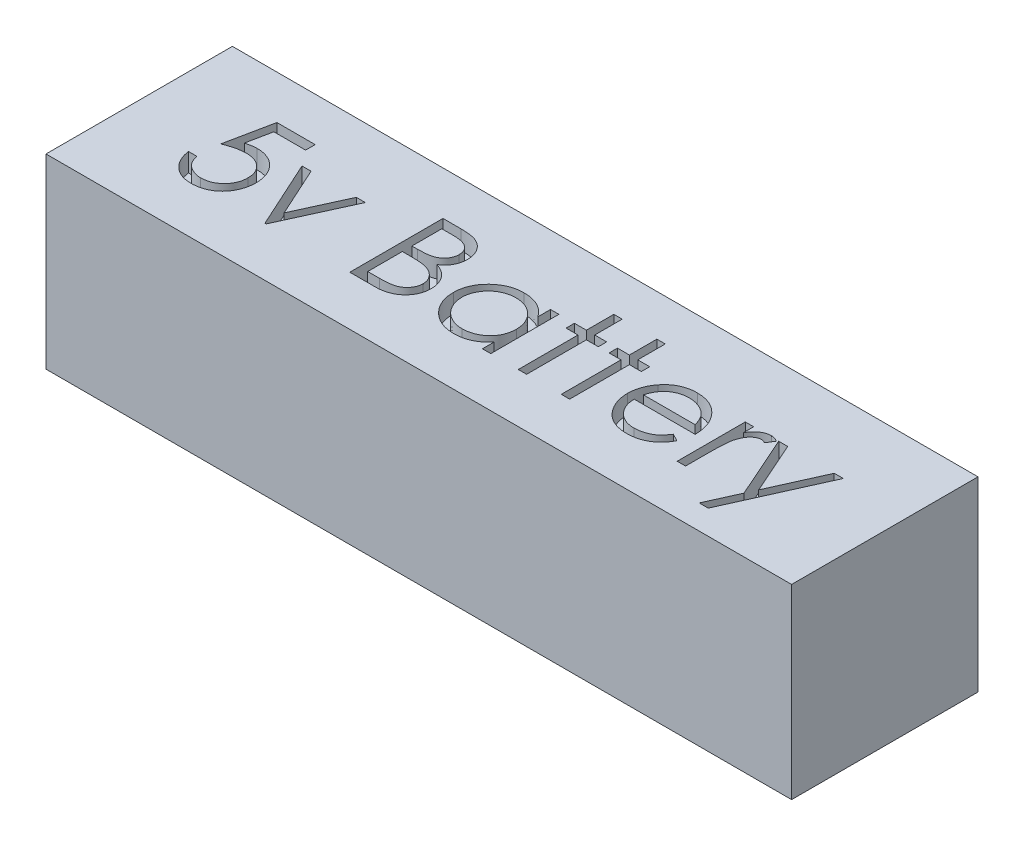
SolidWorks part; units mm, degrees
ref_plane "Front Plane" through (0, 0, 0) normal (0, 0, 1) x (1, 0, 0)
ref_plane "Top Plane" through (0, 0, 0) normal (0, 1, 0) x (1, 0, 0)
ref_plane "Right Plane" through (0, 0, 0) normal (1, 0, 0) x (0, 0, -1)
sketch "Sketch1" plane through (0, 0, 0) normal (0, 1, 0) x (1, 0, 0)
  line L1 (-50.8, -12.7) -> (50.8, -12.7)
  line L2 (-50.8, -12.7) -> (-50.8, 12.7)
  line L3 (-50.8, 12.7) -> (50.8, 12.7)
  line L4 (50.8, -12.7) -> (50.8, 12.7)
  line L5 (-50.8, -12.7) -> (50.8, 12.7) construction
  line L6 (-50.8, 12.7) -> (50.8, -12.7) construction
  point P0 (0, 0)
  dimension "D1" = 25.4
  dimension "D2" = 101.6
extrude "Boss-Extrude1" add sketch "Sketch1" along normal blind 25.4
sketch "Sketch2" plane through (0, 25.4, 0) normal (0, 1, 0) x (1, 0, 0)
  text T0 "5v Battery" font "Century Gothic" height in points 48
extrude "Cut-Extrude1" cut sketch "Sketch2" against normal blind 2.54
